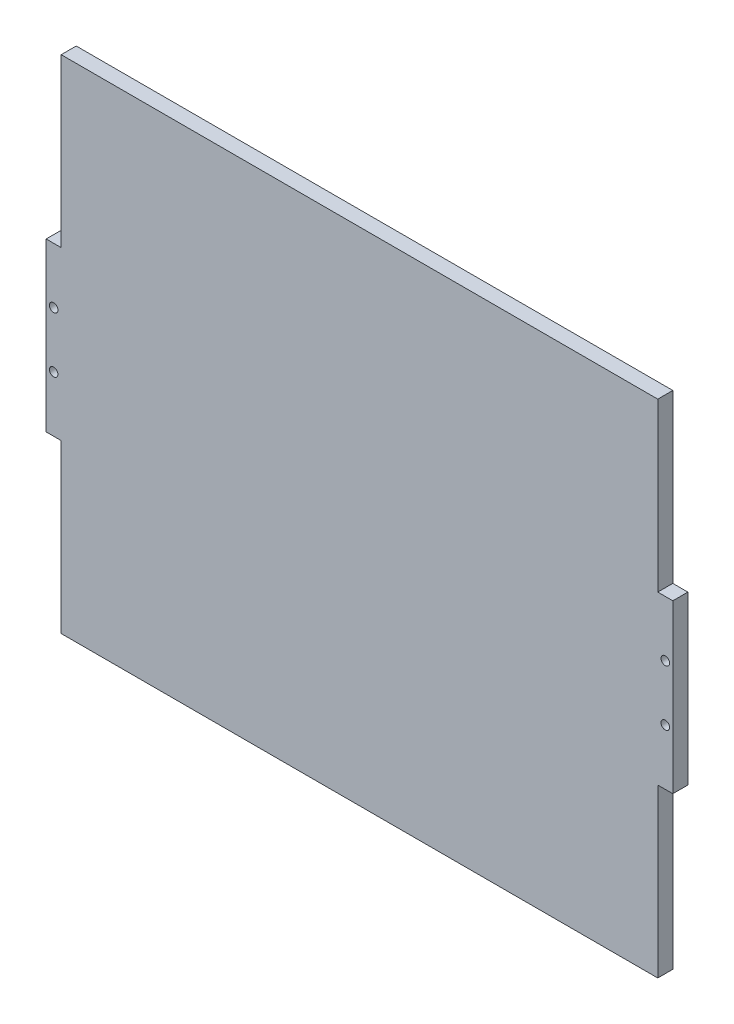
SolidWorks part; units mm, degrees
ref_plane "Front Plane" through (0, 0, 0) normal (0, 0, 1) x (1, 0, 0)
ref_plane "Top Plane" through (0, 0, 0) normal (0, 1, 0) x (1, 0, 0)
ref_plane "Right Plane" through (0, 0, 0) normal (1, 0, 0) x (0, 0, -1)
sketch "Sketch1" plane through (0, 0, 0) normal (0, 0, 1) x (1, 0, 0)
  line L1 (0, 0) -> (500, 0)
  line L2 (0, 0) -> (0, 400)
  line L3 (0, 400) -> (500, 400)
  line L4 (500, 0) -> (500, 400)
  dimension "D1" = 500
  dimension "D2" = 400
extrude "Boss-Extrude1" add sketch "Sketch1" along normal blind 12
sketch "Sketch2" plane through (0, 0, 12) normal (0, 0, 1) x (1, 0, 0)
  line L1 (500, 400) -> (488, 400)
  line L2 (500, 400) -> (500, 266.6667)
  line L3 (500, 266.6667) -> (488, 266.6667)
  line L4 (488, 400) -> (488, 266.6667)
  line L6 (0, 400) -> (12, 400)
  line L7 (0, 400) -> (0, 266.6667)
  line L8 (0, 266.6667) -> (12, 266.6667)
  line L9 (12, 400) -> (12, 266.6667)
  line L10 (0, 0) -> (12, 0)
  line L11 (0, 0) -> (0, 133.3333)
  line L12 (0, 133.3333) -> (12, 133.3333)
  line L13 (12, 0) -> (12, 133.3333)
  line L14 (500, 0) -> (488, 0)
  line L15 (500, 0) -> (500, 133.3333)
  line L16 (500, 133.3333) -> (488, 133.3333)
  line L17 (488, 0) -> (488, 133.3333)
  dimension "D1" = 12
  dimension "D2" = 133.3333
extrude "Cut-Extrude1" cut sketch "Sketch2" against normal blind 12
scale "Scale1" scale about centroid uniform scaling yes scale factor 0.5
hole_wizard "M3 Clearance Slot1" positions "Sketch3" profile "Sketch4" size "M3" standard "ANSI Metric" slot yes end condition up to next
sketch "Sketch3" plane through (0, 0, 3) normal (0, 0, -1) x (-1, 0, 0)
  line L0 (-375, 166.6667) -> (-375, 233.3333) construction
  line L1 (-125, 233.3333) -> (-125, 166.6667) construction
  line L2 (-131, 166.6667) -> (-125, 166.6667) construction
  line L3 (-125, 233.3333) -> (-131, 233.3333) construction
  line L4 (-369, 233.3333) -> (-375, 233.3333) construction
  line L5 (-375, 166.6667) -> (-369, 166.6667) construction
  point P0 (-372, 211.1133)
  point P2 (-372, 188.8867)
  point P4 (-128, 211.11)
  point P6 (-128, 188.89)
  dimension "D1" = 3
  dimension "D2" = 3
  dimension "D3" = 3
  dimension "D4" = 3
  dimension "D5" = 22.2233
  dimension "D6" = 22.2233
  dimension "D7" = 22.22
  dimension "D8" = 22.22
sketch "Sketch4" plane through (372, 211.1133, 3) normal (1, 0, 0) x (0, 1, 0)
  line L0 (0, 0) -> (0, 6)
  line L1 (0, 6) -> (1.7, 6)
  line L2 (1.7, 6) -> (1.7, 0)
  line L5 (1.7, 0) -> (0, 0)
  line L11 (0, -6.35) -> (0, 107.95) construction
  dimension "Thru Hole Dia." = 3.4
  dimension "Thru Hole Depth" = 6
